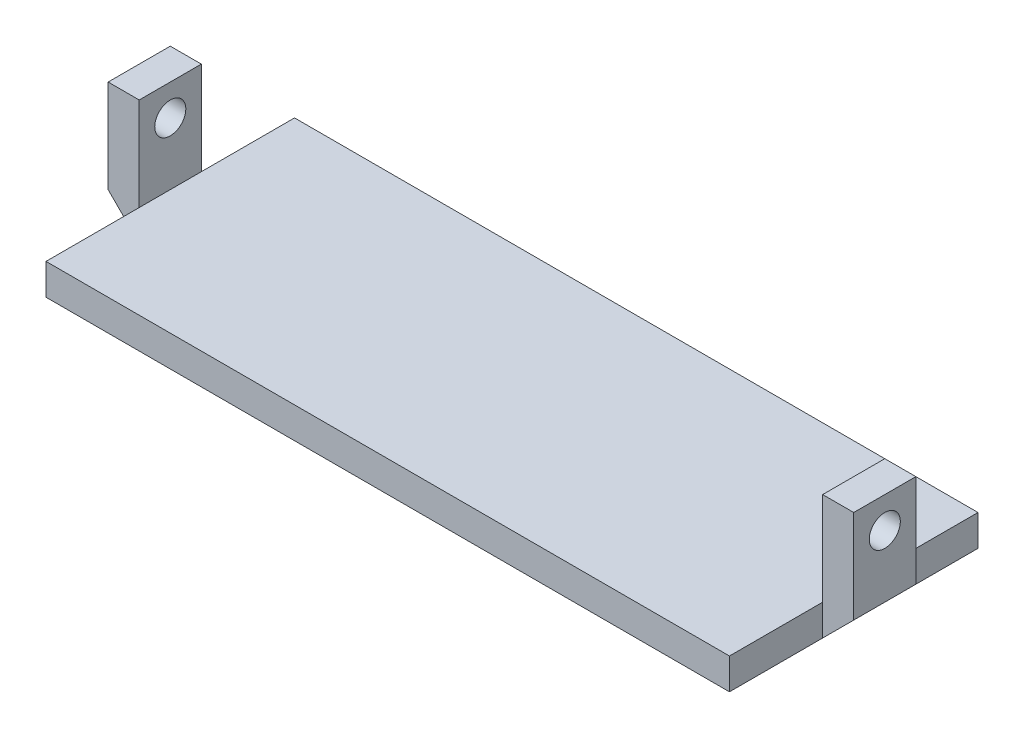
SolidWorks part; units mm, degrees
ref_plane "Front Plane" through (0, 0, 0) normal (0, 0, 1) x (1, 0, 0)
ref_plane "Top Plane" through (0, 0, 0) normal (0, 1, 0) x (1, 0, 0)
ref_plane "Right Plane" through (0, 0, 0) normal (1, 0, 0) x (0, 0, -1)
sketch "Sketch1" plane through (0, 0, 0) normal (0, 1, 0) x (1, 0, 0)
  line L1 (-60, 42.5) -> (60, 42.5)
  line L2 (-60, 42.5) -> (-60, -42.5)
  line L3 (-60, -42.5) -> (60, -42.5)
  line L4 (60, 42.5) -> (60, -42.5)
  line L5 (-60, 42.5) -> (60, -42.5) construction
  line L6 (-60, -42.5) -> (60, 42.5) construction
  point P0 (0, 0)
  dimension "D1" = 120
  dimension "D2" = 85
extrude "Boss-Extrude1" add sketch "Sketch1" along normal blind 5
sketch "Sketch2" plane through (0, 5, 0) normal (0, 1, 0) x (1, 0, 0)
  line L0 (-60, 42.5) -> (-60, -42.5) construction
  line L1 (-60, 17.5) -> (-55, 17.5)
  line L2 (-60, 17.5) -> (-60, 7.5)
  line L3 (-60, 7.5) -> (-55, 7.5)
  line L4 (-55, 17.5) -> (-55, 7.5)
  line L6 (-60, -7.5) -> (-55, -7.5)
  line L7 (-60, -7.5) -> (-60, -17.5)
  line L8 (-60, -17.5) -> (-55, -17.5)
  line L9 (-55, -7.5) -> (-55, -17.5)
  line L10 (-60, 12.5) -> (-55, 12.5) construction
  line L11 (-60, -12.5) -> (-55, -12.5) construction
  line L14 (60, 42.5) -> (-60, 42.5) construction
  line L16 (0, 0) -> (0, -27.3364) construction
  line L17 (60, -12.5) -> (55, -12.5) construction
  line L18 (60, 12.5) -> (55, 12.5) construction
  line L19 (55, -7.5) -> (55, -17.5)
  line L20 (60, -17.5) -> (55, -17.5)
  line L21 (60, -7.5) -> (60, -17.5)
  line L22 (60, -7.5) -> (55, -7.5)
  line L23 (55, 17.5) -> (55, 7.5)
  line L24 (60, 7.5) -> (55, 7.5)
  line L25 (60, 17.5) -> (60, 7.5)
  line L26 (60, 17.5) -> (55, 17.5)
  dimension "D1" = 30
  dimension "D2" = 10
  dimension "D3" = 10
  dimension "D4" = 25
  dimension "D5" = 5
  dimension "D6" = 5
extrude "Boss-Extrude2" add sketch "Sketch2" along normal blind 15
sketch "Sketch3" plane through (-60, 0, 0) normal (-1, 0, 0) x (0, 0, 1)
  line L0 (7.5, 20) -> (17.5, 20) construction
  line L1 (-17.5, 20) -> (-7.5, 20) construction
  line L2 (-17.5, 20) -> (-17.5, 5) construction
  line L3 (7.5, 20) -> (7.5, 5) construction
  circle A0 centre (-12.5, 15) radius 2.5
  circle A1 centre (12.5, 15) radius 2.5
  dimension "D1" = 5
  dimension "D2" = 5
  dimension "D3" = 5
  dimension "D4" = 5
  dimension "D5" = 5
  dimension "D6" = 5
extrude "Cut-Extrude1" cut sketch "Sketch3" against normal through all
sketch "Sketch5" plane through (0, 5, 0) normal (0, 1, 0) x (1, 0, 0)
  line L0 (0, 0) -> (0, -37.502) construction
  line L1 (-60, 42.5) -> (-55, 42.5)
  line L2 (-60, 42.5) -> (-60, 17.5)
  line L3 (-60, 17.5) -> (-55, 17.5)
  line L4 (-55, 42.5) -> (-55, 17.5)
  line L5 (-60, 7.5) -> (-55, 7.5)
  line L6 (-60, 7.5) -> (-60, -7.5)
  line L7 (-60, -7.5) -> (-55, -7.5)
  line L8 (-55, 7.5) -> (-55, -7.5)
  line L9 (-55, -17.5) -> (-60, -17.5)
  line L10 (-55, -17.5) -> (-55, -42.5)
  line L11 (-55, -42.5) -> (-60, -42.5)
  line L12 (-60, -17.5) -> (-60, -42.5)
  line L13 (60, -17.5) -> (60, -42.5)
  line L14 (55, -42.5) -> (60, -42.5)
  line L15 (55, -17.5) -> (55, -42.5)
  line L16 (55, -17.5) -> (60, -17.5)
  line L17 (55, 7.5) -> (55, -7.5)
  line L18 (60, -7.5) -> (55, -7.5)
  line L19 (60, 7.5) -> (60, -7.5)
  line L20 (60, 7.5) -> (55, 7.5)
  line L21 (55, 42.5) -> (55, 17.5)
  line L22 (60, 17.5) -> (55, 17.5)
  line L23 (60, 42.5) -> (60, 17.5)
  line L24 (60, 42.5) -> (55, 42.5)
extrude "Cut-Extrude2" cut sketch "Sketch5" against normal through all
chamfer "Chamfer1" distance 5 angle 45 4 edges at (-60, 0, 12.5) (-60, 0, -12.5) (60, 0, -12.5) (60, 0, 12.5)
sketch "Sketch6" plane through (0, 0, 0) normal (0, -1, 0) x (1, 0, 0)
  line L0 (-55, 42.5) -> (-55, 17.5) construction
  line L1 (-55, -42.5) -> (55, -42.5)
  line L2 (-55, -42.5) -> (-55, -7.5)
  line L3 (-55, -7.5) -> (55, -7.5)
  line L4 (55, -42.5) -> (55, -7.5)
  line L5 (55, 42.5) -> (-55, 42.5)
  line L6 (55, 42.5) -> (55, 32.5)
  line L7 (55, 32.5) -> (-55, 32.5)
  line L8 (-55, 42.5) -> (-55, 32.5)
  line L10 (-60, 17.5) -> (-55, 17.5) construction
  line L12 (-60, -7.5) -> (-55, -7.5)
  line L13 (-60, -7.5) -> (-60, -42.5)
  line L14 (-60, -42.5) -> (-55, -42.5)
  line L15 (-55, -7.5) -> (-55, -42.5)
  line L16 (55, -42.5) -> (60, -42.5)
  line L17 (55, -42.5) -> (55, -7.5)
  line L18 (55, -7.5) -> (60, -7.5)
  line L19 (60, -42.5) -> (60, -7.5)
  line M2 (-55, 42.5) -> (-55, 17.5)
  line M5 (-55, -7.5) -> (-55, -17.5)
  line M6 (-55, -17.5) -> (-55, -42.5)
  line M7 (-55, -42.5) -> (55, -42.5)
  line M8 (55, -42.5) -> (55, -17.5)
  line M9 (55, -17.5) -> (55, -7.5)
  line M12 (55, 17.5) -> (55, 42.5)
  line M13 (55, 42.5) -> (-55, 42.5)
  dimension "D1" = 15
extrude "Cut-Extrude3" cut sketch "Sketch6" against normal through all contours L3 M5 M6 M7 M8 M9 | L13 L14 L12 M6 M5 | L7 M12 M13 M2 | L16 L19 L18 M9 M8
